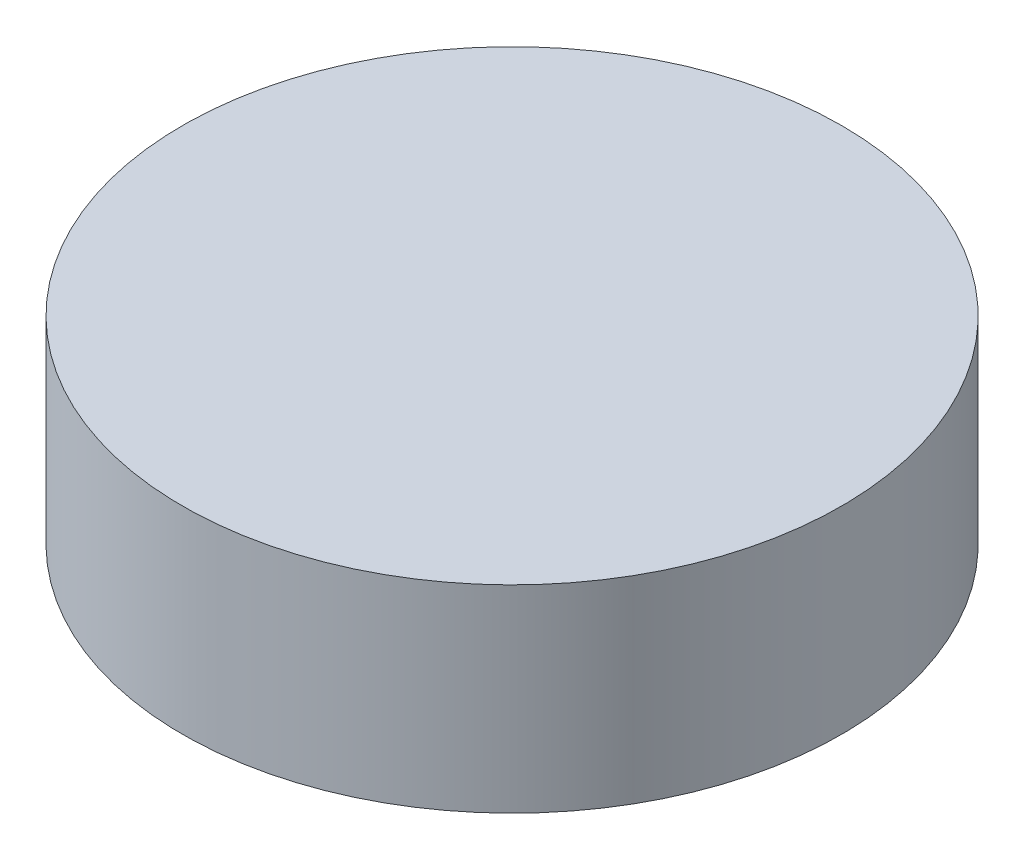
SolidWorks part; units mm, degrees
ref_plane "Front Plane" through (0, 0, 0) normal (0, 0, 1) x (1, 0, 0)
ref_plane "Top Plane" through (0, 0, 0) normal (0, 1, 0) x (1, 0, 0)
ref_plane "Right Plane" through (0, 0, 0) normal (1, 0, 0) x (0, 0, -1)
sketch "Sketch1" plane through (0, 0, 0) normal (0, 1, 0) x (1, 0, 0)
  circle A0 centre (0, 0) radius 127
extrude "Boss-Extrude1" add sketch "Sketch1" along normal blind 76.2
